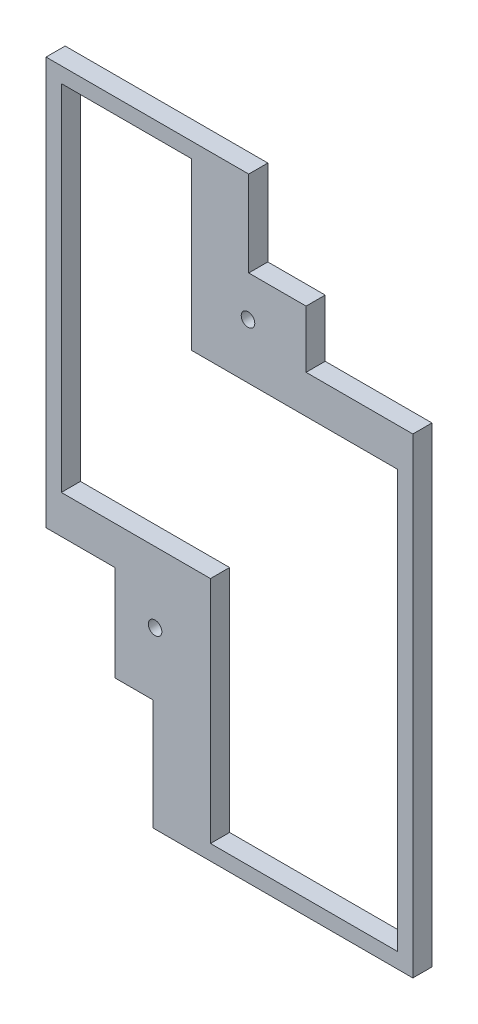
SolidWorks part; units mm, degrees
ref_plane "Front Plane" through (0, 0, 0) normal (0, 0, 1) x (1, 0, 0)
ref_plane "Top Plane" through (0, 0, 0) normal (0, 1, 0) x (1, 0, 0)
ref_plane "Right Plane" through (0, 0, 0) normal (1, 0, 0) x (0, 0, -1)
sketch "Sketch1" plane through (0, 0, 0) normal (0, 0, 1) x (1, 0, 0)
  line L0 (40.64, 122.682) -> (40.64, 94.234)
  line L1 (-26.67, 122.682) -> (40.64, 122.682)
  line L2 (-26.67, 122.682) -> (-26.67, -12.7)
  line L3 (8.89, -81.28) -> (95.1484, -81.28)
  line L4 (95.1484, 75.184) -> (95.1484, -81.28)
  line L5 (40.64, 94.234) -> (59.69, 94.234)
  line L6 (59.69, 94.234) -> (59.69, 75.184)
  line L7 (59.69, 75.184) -> (95.1484, 75.184)
  line L8 (-26.67, -12.7) -> (-3.81, -12.7)
  line L9 (-3.81, -12.7) -> (-3.81, -44.45)
  line L10 (-3.81, -44.45) -> (8.89, -44.45)
  line L11 (8.89, -44.45) -> (8.89, -81.28)
  line L12 (21.59, 117.602) -> (-21.59, 117.602) construction
  line L13 (27.94, -76.2) -> (90.0684, -76.2) construction
  line L14 (90.0684, -76.2) -> (90.0684, 62.484) construction
  line L15 (-21.59, 117.602) -> (-21.59, 0) construction
  line L16 (27.94, 62.484) -> (27.94, -76.2) construction
  line L17 (-21.59, 0) -> (21.59, 0) construction
  line L18 (90.0684, 62.484) -> (27.94, 62.484) construction
  line L20 (21.59, 0) -> (21.59, 117.602) construction
  line L21 (90.0684, 62.484) -> (27.94, 62.484) construction
  line L22 (27.94, 62.484) -> (27.94, -76.2) construction
  line L23 (27.94, -76.2) -> (90.0684, -76.2) construction
  line L24 (90.0684, -76.2) -> (90.0684, 62.484) construction
  line L25 (21.59, 0) -> (21.59, 117.602) construction
  line L26 (-21.59, 0) -> (21.59, 0) construction
  line L27 (-21.59, 117.602) -> (-21.59, 0) construction
  line L28 (21.59, 117.602) -> (-21.59, 117.602) construction
  line L29 (90.0684, 62.484) -> (27.94, 62.484)
  line L30 (27.94, 0) -> (27.94, -76.2)
  line L31 (27.94, -76.2) -> (90.0684, -76.2)
  line L32 (90.0684, -76.2) -> (90.0684, 62.484)
  line L33 (21.59, 62.484) -> (21.59, 117.602)
  line L34 (-21.59, 0) -> (21.59, 0)
  line L35 (-21.59, 117.602) -> (-21.59, 0)
  line L36 (21.59, 117.602) -> (-21.59, 117.602)
  line L37 (27.94, 62.484) -> (21.59, 62.484)
  line L38 (21.59, 0) -> (27.94, 0)
  point P28 (40.64, 75.184)
  point P29 (10.251, -24.1623)
  dimension "D1" = 5.08
  dimension "D2" = 5.08
  dimension "D3" = 5.08
  dimension "D4" = 5.08
  dimension "D5" = 19.05
  dimension "D6" = 31.75
  dimension "D7" = 12.7
  dimension "D8" = 44.45
  dimension "D9" = 12.7
  dimension "D10" = 31.75
  dimension "D11" = 19.05
  dimension "D12" = 38.1
extrude "Boss-Extrude1" add sketch "Sketch1" along normal blind 6.35
hole_wizard "#8 Clearance Hole1" positions "Sketch2" profile "Sketch3" hole size "#8" standard "ANSI Inch" end condition through all
sketch "Sketch2" plane through (0, 0, 6.35) normal (0, 0, 1) x (1, 0, 0)
  point P0 (9.5383, -23.3764)
  point P2 (40.4028, 80.7285)
sketch "Sketch3" plane through (9.5383, -23.3764, 6.35) normal (1, 0, 0) x (0, -1, 0)
  line L0 (0, 0) -> (0, 6.35)
  line L1 (0, 6.35) -> (2.2479, 6.35)
  line L2 (2.2479, 6.35) -> (2.2479, 0)
  line L5 (2.2479, 0) -> (0, 0)
  line L11 (0, -6.35) -> (0, 107.95) construction
  dimension "Thru Hole Dia." = 4.4958
  dimension "Thru Hole Depth" = 6.35
